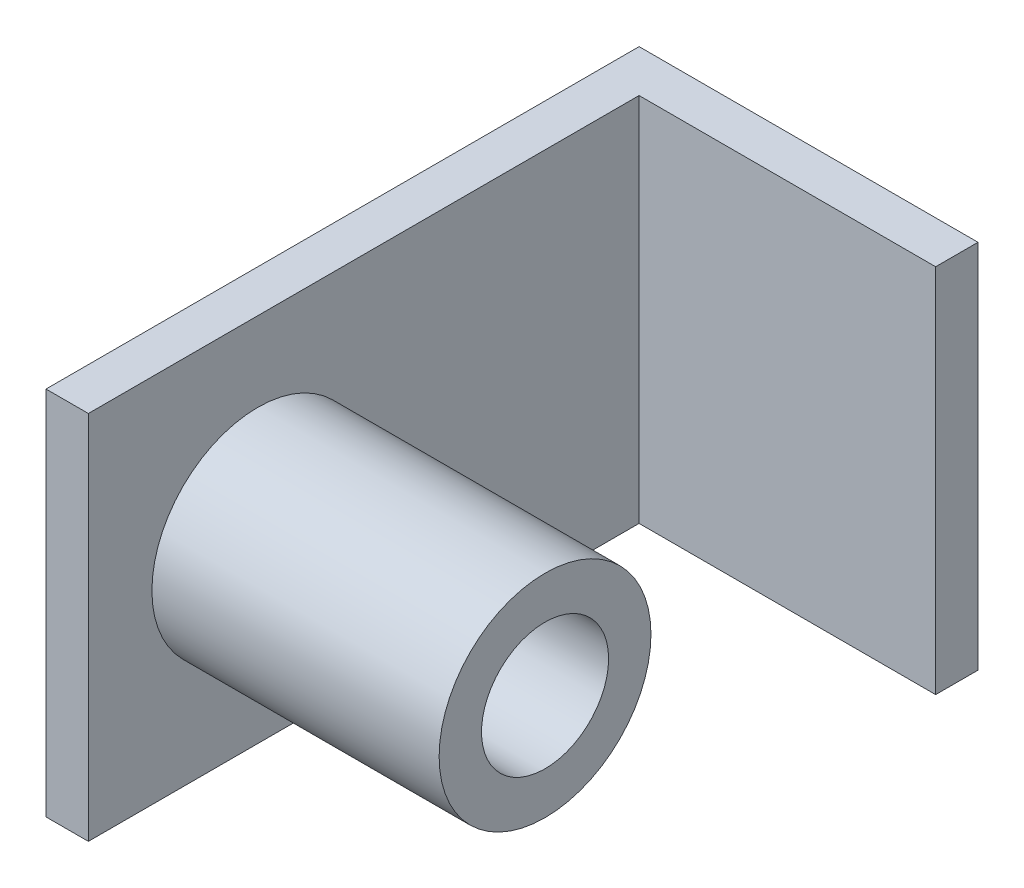
SolidWorks part; units mm, degrees
material "ABS"
ref_plane "Front Plane" through (0, 0, 0) normal (0, 0, 1) x (1, 0, 0)
ref_plane "Top Plane" through (0, 0, 0) normal (0, 1, 0) x (1, 0, 0)
ref_plane "Right Plane" through (0, 0, 0) normal (1, 0, 0) x (0, 0, -1)
sketch "Sketch2" plane through (0, 0, 0) normal (0, 1, 0) x (1, 0, 0)
  line L0 (101.6, 0) -> (0, 0)
  line L1 (0, 0) -> (0, -177.8)
  line L2 (0, -177.8) -> (12.7, -177.8)
  line L3 (12.7, -177.8) -> (12.7, -12.7)
  line L4 (12.7, -12.7) -> (101.6, -12.7)
  line L5 (101.6, -12.7) -> (101.6, 0)
  dimension "D1" = 177.8
  dimension "D2" = 101.6
  dimension "D3" = 12.7
  dimension "D4" = 12.7
extrude "Boss-Extrude1" add sketch "Sketch2" along normal blind 111.092
sketch "Sketch3" plane through (0, 0, 0) normal (0, 0, -1) x (-1, 0, 0)
  line L0 (-50.8, 0) -> (-50.8, 111.092) construction
  line L1 (-101.6, 0) -> (0, 0) construction
  line L2 (-101.6, 111.092) -> (0, 111.092) construction
  line L3 (-101.6, 55.546) -> (0, 55.546) construction
  line L4 (-101.6, 111.092) -> (-101.6, 0) construction
  line L5 (0, 111.092) -> (0, 0) construction
  circle A0 centre (-50.8, 55.546) radius 12.7
  dimension "D1" = 25.4
extrude "Boss-Extrude2" add sketch "Sketch3" along normal blind 25.4
sketch "Sketch4" plane through (12.7, 0, 0) normal (1, 0, 0) x (0, 0, -1)
  line L0 (-177.8, 55.546) -> (0, 55.546) construction
  line L1 (-177.8, 111.092) -> (-177.8, 0) construction
  line L2 (0, 111.092) -> (0, 0) construction
  circle A1 centre (-127, 55.546) radius 31.75
  circle A2 centre (-127, 55.546) radius 19.05
  dimension "D1" = 63.5
  dimension "D3" = 38.1
  dimension "D2" = 127
extrude "Boss-Extrude3" add sketch "Sketch4" along normal blind 86.106
